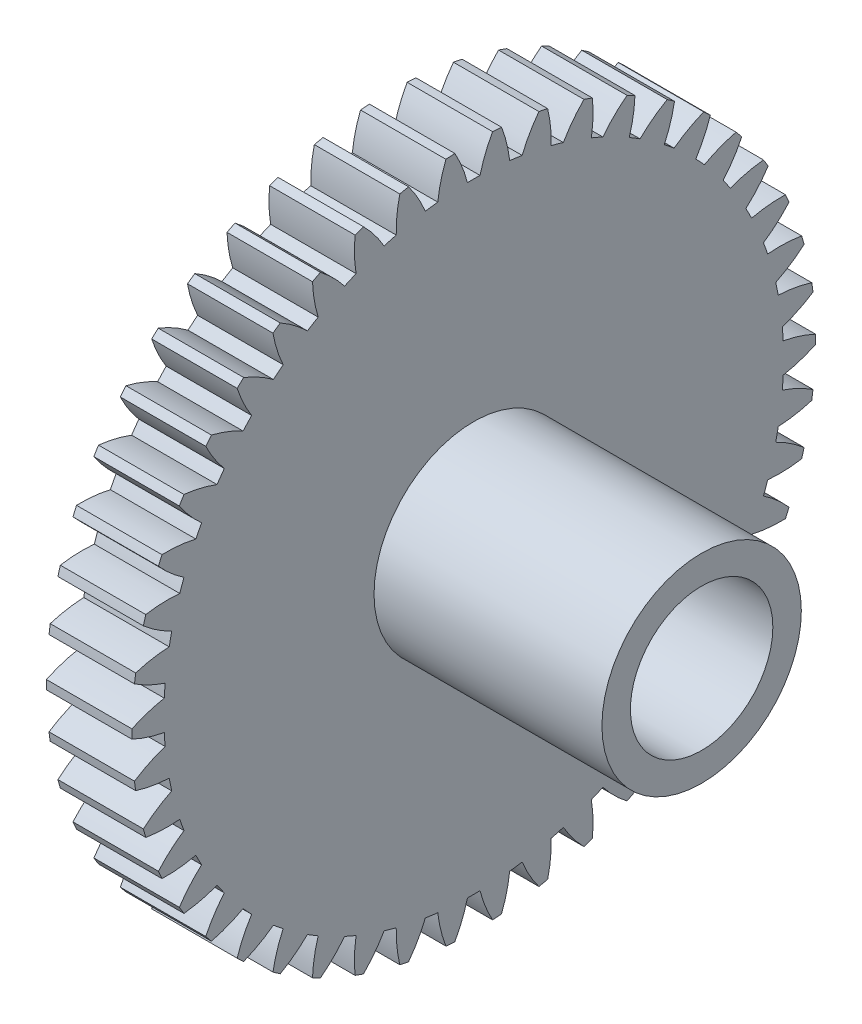
SolidWorks part; units mm, degrees
ref_plane "Plane1" through (0, 0, 0) normal (0, 0, 1) x (1, 0, 0)
ref_plane "Plane2" through (0, 0, 0) normal (0, 1, 0) x (1, 0, 0)
ref_plane "Plane3" through (0, 0, 0) normal (1, 0, 0) x (0, 0, -1)
other "Configuration Table"
sketch "HoldingSke" plane through (0, 0, 0) normal (0, 1, 0) x (1, 0, 0)
  line L0 (0, 0) -> (0.6947, -0.7193)
  line L1 (-15, 0) -> (100, 0) construction
  line L2 (0, 0) -> (-2.1039, 2.3779)
  line L3 (0, 0) -> (-11.863, 4.5341)
  line L4 (0, 0) -> (5.9991, 6.2122)
  line L5 (0, 0) -> (-46.8476, -17.4728)
  line L6 (0, 0) -> (-4.9738, -3.3558)
  line L7 (-2.1039, 2.3779) -> (8.6587, 51.2062)
  line L8 (-76.2, 54.61) -> (-75.2, 54.61)
  line L9 (-71.009, 38.7566) -> (-53.1078, 45.2721)
  line L10 (-76.2, 71.12) -> (104.1128, 71.12)
  line L11 (0, 0) -> (-6, 0)
  line L12 (-76.2, 101.6) -> (-76.162, 101.6)
  line L13 (24.9733, 27.94) -> (52.9518, 28.4284)
  line L14 (24.9733, 27.94) -> (24.9743, 27.94)
  line L15 (24.9733, 27.94) -> (100.4006, 29.5858)
  line L16 (-63.627, -1) -> (-12.827, -1)
  circle A0 centre (0, 0) radius 3
  circle A1 centre (0, 0) radius 21.749
  circle A2 centre (0, 0) radius 37.5
  circle A3 centre (0, 0) radius 3
  dimension "MHD" = 43.498
  dimension "Hub_dia" = 75
  dimension "Bore" = 6
  dimension "MBD" = 6
  dimension "Num_teeth" = 46
  dimension "Pitch" = 1
  dimension "Overall_len" = 50
  dimension "Show_teeth" = 46
  dimension "Thickness" = 6
  dimension "OAL" = 50.0004
  dimension "T_dim" = 1
  dimension "Ap" = 20
  dimension "H" = 19.05
  dimension "Pitch_radius" = 180.3128
  dimension "Width" = 6
  dimension "Backlash" = 0.038
  dimension "Addendum_fac" = 1
  dimension "Dedendum_fac" = 1.25
  dimension "Clearance_fac" = 0.25
  dimension "Dedendum_add" = 0.001
  dimension "Module" = 1
sketch "BasProSke" plane through (0, 0, 0) normal (0, 1, 0) x (1, 0, 0)
  line L0 (-10, 0) -> (60, 0) construction
  line L1 (0, 0) -> (0, 24)
  line L2 (0, 0) -> (6, 0)
  line L3 (6, 0) -> (6, 24)
  line L4 (6, 24) -> (0, 24)
  dimension "Thickness" = 6
  dimension "Diameter" = 48
revolve "Base-Revolve" add sketch "BasProSke" angle 360 about L0
sketch "TooCutSke" plane through (0, 0, 0) normal (1, 0, 0) x (0, 0, -1)
  line L1 (0, 0) -> (0, 107) construction
  line L2 (0, 0) -> (-0.8517, 22.9842) construction
  line L3 (0, 0) -> (-3.1376, 45.8703) construction
  line L4 (-0.8517, 22.9842) -> (-1.5688, 22.9352) construction
  arc A0 (0.4415, 21.7445) -> (-0.4415, 21.7445) centre (0, 0) ccw
  arc A1 (1.3382, 23.9881) -> (-1.3382, 23.9881) centre (0, 0) ccw
  circle A2 centre (0, 0) radius 23 construction
  circle A3 centre (0, 0) radius 21.6129 construction
  arc A4 (-0.4415, 21.7445) -> (-1.3382, 23.9881) centre (-9.3589, 19.4815) ccw
  arc A5 (1.3382, 23.9881) -> (0.4415, 21.7445) centre (9.3589, 19.4815) ccw
  dimension "Root_dia" = 43.498
  dimension "Overcut_dia" = 48.0508
  dimension "Pitch_dia" = 46
  dimension "Base_dia" = 43.2259
  dimension "Flank_rad" = 9.2
  dimension "Half_ang" = 3.913
  dimension "Half_CT" = 0.7187
extrude "ToothCut" cut sketch "TooCutSke" along normal through all
fillet "Breaks" [suppressed] radius 0.02
fillet "RootFillets" [suppressed] radius 0.251
pattern_circular "TeethCuts" count 46 every 7.826 about axis through (-10, 0, 0) along (1, 0, 0) of "ToothCut", "RootFillets", "Breaks"
sketch "HubNeaOneSke" plane through (0, 0, 0) normal (-1, 0, 0) x (0, 0, 1)
  circle A0 centre (0, 0) radius 21.749
  dimension "Diameter" = 43.498
extrude "HubNearOne" [suppressed] add sketch "HubNeaOneSke" along normal blind 44.0004
sketch "HubNeaBotSke" plane through (0, 0, 0) normal (-1, 0, 0) x (0, 0, 1)
  circle A0 centre (0, 0) radius 21.749
  dimension "Diameter" = 43.498
extrude "HubNearBoth" [suppressed] add sketch "HubNeaBotSke" along normal blind 22.0002
ref_plane "FarPln" through (6, 0, 0) normal (1, 0, 0) x (0, 0, -1)
sketch "HubFarSke" plane through (6, 0, 0) normal (1, 0, 0) x (0, 0, -1)
  circle A0 centre (0, 0) radius 21.749
  dimension "Diameter" = 43.498
extrude "HubFar" [suppressed] add sketch "HubFarSke" along normal blind 22.0002
sketch "KeySke" plane through (0, 0, 0) normal (1, 0, 0) x (0, 0, -1)
  line L0 (-1, 0) -> (-1, 4)
  line L1 (-1, 4) -> (1, 4)
  line L2 (1, 4) -> (1, 0)
  line L3 (0, 0) -> (0, 34) construction
  line L4 (-1, 0) -> (1, 0)
  dimension "Offset" = 4
  dimension "Width" = 2
extrude "Keyway" [suppressed] cut sketch "KeySke" along normal mid plane 100.0008
pattern_circular "Keyway2" [suppressed] count 2 every 90 about axis through (-10, 0, 0) along (1, 0, 0)
sketch "Sketch2" plane through (6, 0, 0) normal (1, 0, 0) x (0, 0, -1)
  circle A0 centre (0, 0) radius 5
  circle A1 centre (0, 0) radius 7
  dimension "D1" = 10
  dimension "D2" = 14
extrude "Boss-Extrude1" add sketch "Sketch2" along normal blind 16
sketch "Sketch3" plane through (0, 0, 0) normal (-1, 0, 0) x (0, 0, 1)
  circle A0 centre (0, 0) radius 15
  dimension "D1" = 30
extrude "Cut-Extrude2" cut sketch "Sketch3" against normal blind 3 contours A0
equation "' \"Module@HoldingSke\" = 6.35"
equation "' \"Num_teeth@HoldingSke\" = 12"
equation "' \"Ap@HoldingSke\" =  20"
equation "' \"Ap@HoldingSke\" = 20"
equation "' \"Width@HoldingSke\" = 0.5 * 25.4"
equation "' \"Hub_dia@HoldingSke\"= 1 * 25.4"
equation "' \"Hub_dia@HoldingSke\" = 1 * 25.4"
equation "' \"Overall_len@HoldingSke\" = 1.0 * 25.4"
equation "' \"Bore@HoldingSke\" = 0.75 * 25.4"
equation "' \"T_dim@HoldingSke\" = 0.1 * 25.4"
equation "' \"Width@KeySke\" = 0.25 * 25.4"
equation "' \"Show_teeth@HoldingSke\" = 13"
equation "' \"Backlash@HoldingSke\" = 0.009 * 25.4"
equation "' \"Addendum_fac@HoldingSke\" = 1.0"
equation "' \"Dedendum_fac@HoldingSke\" = 1.25"
equation "' \"Dedendum_add@HoldingSke\" = 0.00005 * 25.4"
equation "' \"Clearance_fac@HoldingSke\" = 0.25"
equation "\"Pitch@HoldingSke\" = 1 / \"Module@HoldingSke\""
equation "\"Overcut_dia@TooCutSke\" = (\"Num_teeth@HoldingSke\" + 2 * \"Addendum_fac@HoldingSke\") / \"Pitch@HoldingSke\" + 0.002 * 25.4"
equation "\"Pitch_dia@TooCutSke\" = \"Num_teeth@HoldingSke\" / \"Pitch@HoldingSke\""
equation "\"Base_dia@TooCutSke\" = \"Num_teeth@HoldingSke\" / \"Pitch@HoldingSke\" * cos((\"Ap@HoldingSke\"  * 3.14159265 / 180))"
equation "\"Root_dia@TooCutSke\" = (\"Num_teeth@HoldingSke\" + 2) / \"Pitch@HoldingSke\" - 2 * (\"Addendum_fac@HoldingSke\" + \"Dedendum_fac@HoldingSke\") / \"Pitch@HoldingSke\" - \"Dedendum_add@HoldingSke\" * 2"
equation "\"Half_ang@TooCutSke\" = 180 / \"Num_teeth@HoldingSke\""
equation "\"Half_CT@TooCutSke\" = \"Num_teeth@HoldingSke\" / \"Pitch@HoldingSke\" * sin((3.14159265 / 2 / \"Num_teeth@HoldingSke\")) / 2 - 7 * \"Backlash@HoldingSke\" / 4"
equation "\"Flank_rad@TooCutSke\" = \"Num_teeth@HoldingSke\" / \"Pitch@HoldingSke\" / 5"
equation "\"Radius@RootFillets\" = \"Clearance_fac@HoldingSke\" / \"Pitch@HoldingSke\" + \"Dedendum_add@HoldingSke\""
equation "\"Break_rad@Breaks\" = 0.02 / \"Pitch@HoldingSke\""
equation "\"Thickness@HoldingSke\" = \"Width@HoldingSke\""
equation "\"OAL@HoldingSke\" = \"Thickness@HoldingSke\""
equation "\"MHD@HoldingSke\" = (\"Num_teeth@HoldingSke\" + 2) / \"Pitch@HoldingSke\" - 2 * (\"Addendum_fac@HoldingSke\" + \"Dedendum_fac@HoldingSke\")  / \"Pitch@HoldingSke\" - \"Dedendum_add@HoldingSke\" * 2"
equation "\"MBD@HoldingSke\" = (\"Num_teeth@HoldingSke\" + 2) / \"Pitch@HoldingSke\" - 2 * (\"Addendum_fac@HoldingSke\" + \"Dedendum_fac@HoldingSke\")  / \"Pitch@HoldingSke\" - \"Dedendum_add@HoldingSke\" * 2 - 0.002 * 25.4"
equation "\"MHD@HoldingSke\" = ((sgn( \"MHD@HoldingSke\" - \"Hub_dia@HoldingSke\" )-1)*( \"MHD@HoldingSke\" - \"Hub_dia@HoldingSke\" ))/-2+ \"Hub_dia@HoldingSke\""
equation "\"MBD@HoldingSke\" = ((sgn( \"MBD@HoldingSke\" - \"Bore@HoldingSke\" )-1)*( \"MBD@HoldingSke\" - \"Bore@HoldingSke\" ))/-2+ \"Bore@HoldingSke\""
equation "\"OAL@HoldingSke\" = ((sgn( \"OAL@HoldingSke\" - \"Overall_len@HoldingSke\" )+1)*( \"OAL@HoldingSke\" - \"Overall_len@HoldingSke\" ))/2 + \"Overall_len@HoldingSke\" + 0.000002 * 25.4"
equation "\"Num_teeth@TeethCuts\" = int( \"Show_teeth@HoldingSke\" ) + 1"
equation "\"Num_teeth@TeethCuts\" = ((sgn( \"Num_teeth@TeethCuts\" - \"Num_teeth@HoldingSke\" )-1)*( \"Num_teeth@TeethCuts\" - \"Num_teeth@HoldingSke\" ))/-2+ \"Num_teeth@HoldingSke\""
equation "\"Num_teeth@TeethCuts\" = ((sgn( \"Num_teeth@TeethCuts\" - 2.0)+1)*( \"Num_teeth@TeethCuts\" - 2.0))/2 +2.0"
equation "\"Angle@TeethCuts\" = 360.0 / \"Num_teeth@HoldingSke\""
equation "\"Diameter@BasProSke\" = (\"Num_teeth@HoldingSke\" + 2 * \"Addendum_fac@HoldingSke\") / \"Pitch@HoldingSke\""
equation "\"Thickness@BasProSke\"  = \"Thickness@HoldingSke\""
equation "' \"Fillet_rad@BasProSke\" =  \"Thickness@HoldingSke\" * 0.05"
equation "' \"Fillet_rad@BasProSke\" = \"Thickness@HoldingSke\" * 0.05"
equation "\"MHD@HoldingSke\" = ((sgn( \"MHD@HoldingSke\" - \"Root_dia@TooCutSke\" )-1)*( \"MHD@HoldingSke\" - \"Root_dia@TooCutSke\" ))/-2+ \"Root_dia@TooCutSke\""
equation "\"Diameter@HubNeaOneSke\" = \"MHD@HoldingSke\""
equation "\"Length@HubNearOne\" = \"OAL@HoldingSke\" - \"Thickness@BasProSke\""
equation "\"Diameter@HubNeaBotSke\" = \"MHD@HoldingSke\""
equation "\"Length@HubNearBoth\" = ( \"OAL@HoldingSke\" - \"Thickness@BasProSke\" ) / 2.0"
equation "\"Thickness@FarPln\" = \"Thickness@BasProSke\""
equation "\"Diameter@HubFarSke\" = \"MHD@HoldingSke\""
equation "\"Length@HubFar\" = ( \"OAL@HoldingSke\" - \"Thickness@BasProSke\" ) / 2.0"
equation "\"D1@Keyway\"= \"OAL@HoldingSke\" * 2.0"
equation "\"Offset@KeySke\" = \"T_dim@HoldingSke\" + \"MBD@HoldingSke\" / 2.0"
